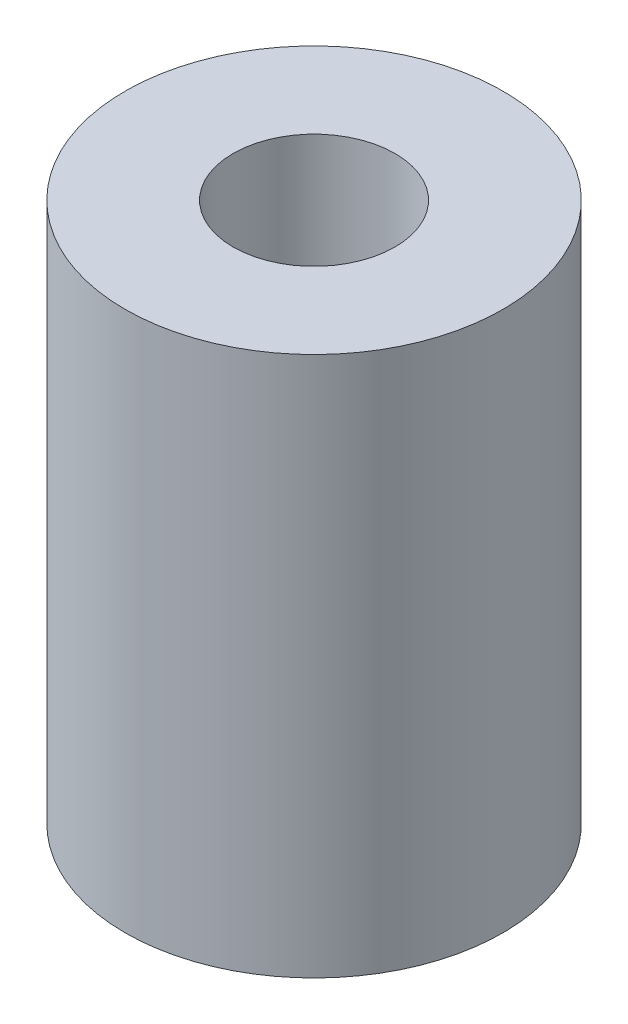
SolidWorks part; units mm, degrees
ref_plane "Front Plane" through (0, 0, 0) normal (0, 0, 1) x (1, 0, 0)
ref_plane "Top Plane" through (0, 0, 0) normal (0, 1, 0) x (1, 0, 0)
ref_plane "Right Plane" through (0, 0, 0) normal (1, 0, 0) x (0, 0, -1)
sketch "Sketch1" plane through (0, 0, 0) normal (0, 1, 0) x (1, 0, 0)
  circle A0 centre (0, 0) radius 1.5
  circle A1 centre (0, 0) radius 3.5
extrude "Boss-Extrude1" add sketch "Sketch1" along normal blind 10
